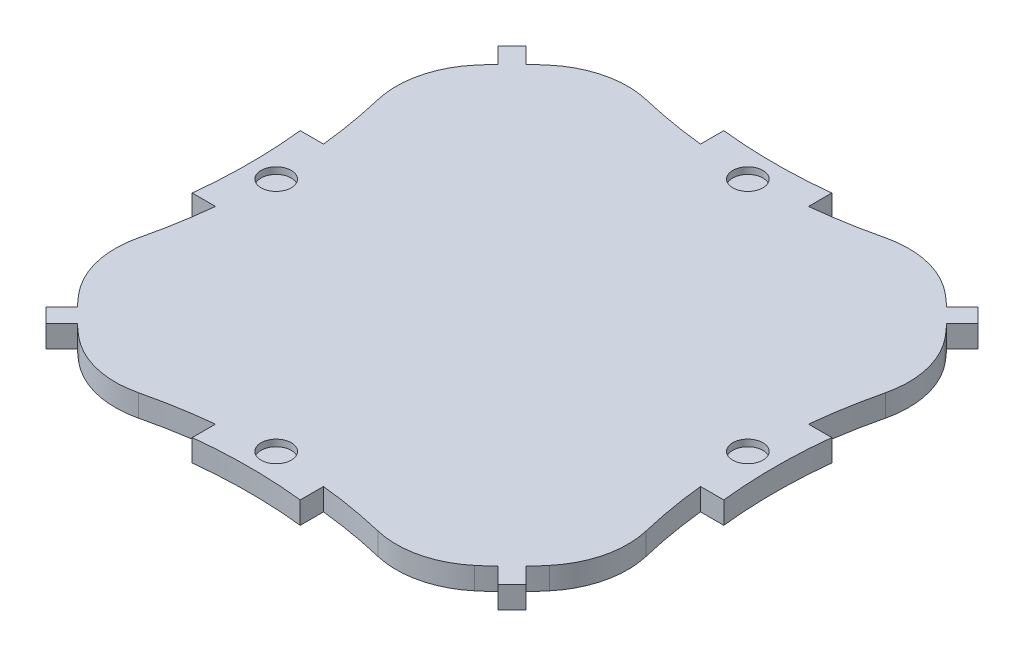
SolidWorks part; units mm, degrees
ref_plane "Front Plane" through (0, 0, 0) normal (0, 0, 1) x (1, 0, 0)
ref_plane "Top Plane" through (0, 0, 0) normal (0, 1, 0) x (1, 0, 0)
ref_plane "Right Plane" through (0, 0, 0) normal (1, 0, 0) x (0, 0, -1)
sketch "Sketch1" plane through (0, 0, 0) normal (0, 1, 0) x (1, 0, 0)
  circle A0 centre (0, 0) radius 35.433
  arc A4 (26.8199, -23.3497) -> (27.3308, -22.7495) centre (0, 0) ccw construction
  dimension "D1" = 0.127
extrude "Boss-Extrude1" add sketch "Sketch1" along normal blind 2.54
sketch "Sketch2" plane through (0, 2.54, 0) normal (0, 1, 0) x (1, 0, 0)
  circle A0 centre (0, 86.7779) radius 59.1581
  arc A2 (-13.8636, 29.3978) -> (-6.9175, 28.1535) centre (0, 86.7779) ccw construction
  dimension "D1" = 0.127
extrude "Cut-Extrude1" cut sketch "Sketch2" against normal through all
sketch "Sketch3" plane through (0, 0, 0) normal (0, -1, 0) x (-1, 0, 0)
  line L0 (-6.35, 30.6448) -> (-6.35, 28.658) construction
  line L1 (6.223, 22.3413) -> (-6.223, 22.3413)
  line L2 (6.223, 22.3413) -> (6.223, 30.6306)
  line L4 (-6.223, 22.3413) -> (-6.223, 30.6306)
  line L5 (6.223, 22.3413) -> (-2.4472, 30.3398) construction
  line L6 (2.4472, 30.3398) -> (-6.223, 22.3413) construction
  arc A0 (-6.35, 30.6448) -> (6.35, 30.6448) centre (0, 86.7779) ccw construction
  arc A1 (-6.223, 30.6306) -> (6.223, 30.6306) centre (0, 86.7779) ccw
  point P0 (0, 28.0822)
  dimension "D1" = 0.127
extrude "Boss-Extrude3" add sketch "Sketch3" against normal blind 2.54
sketch "Sketch4" plane through (0, 2.54, 0) normal (0, 1, 0) x (1, 0, 0)
  circle A1 centre (0, 27.178) radius 1.7399
  point P1 (0, 0)
  dimension "D1" = 27.178
  dimension "D2" = 3.4798
extrude "Cut-Extrude2" cut sketch "Sketch4" against normal blind 0.762
fillet "Fillet1" radius 10.287 2 edges at (18.1049, 1.27, -30.4583) (-18.1049, 1.27, -30.4583)
sketch "Sketch5" plane through (0, 2.54, 0) normal (0, 1, 0) x (1, 0, 0)
  line L0 (0, 0) -> (26.851, 26.851)
  line L1 (0, 0) -> (0, 13.1801) construction
  arc A0 (-22.8058, 27.1181) -> (22.8058, 27.1181) centre (0, 0) ccw construction
  dimension "D1" = 45
  dimension "D2" = 2.54
extrude "Extrude-Thin1" add sketch "Sketch5" against normal blind 2.54 thin thin type mid plane wall 2.286
pattern_circular "CirPattern1" count 4 over 360 about axis through (0, 0, 0) along (0, 1, 0) of "Cut-Extrude1", "Boss-Extrude3", "Cut-Extrude2", "Fillet1", "Extrude-Thin1"
